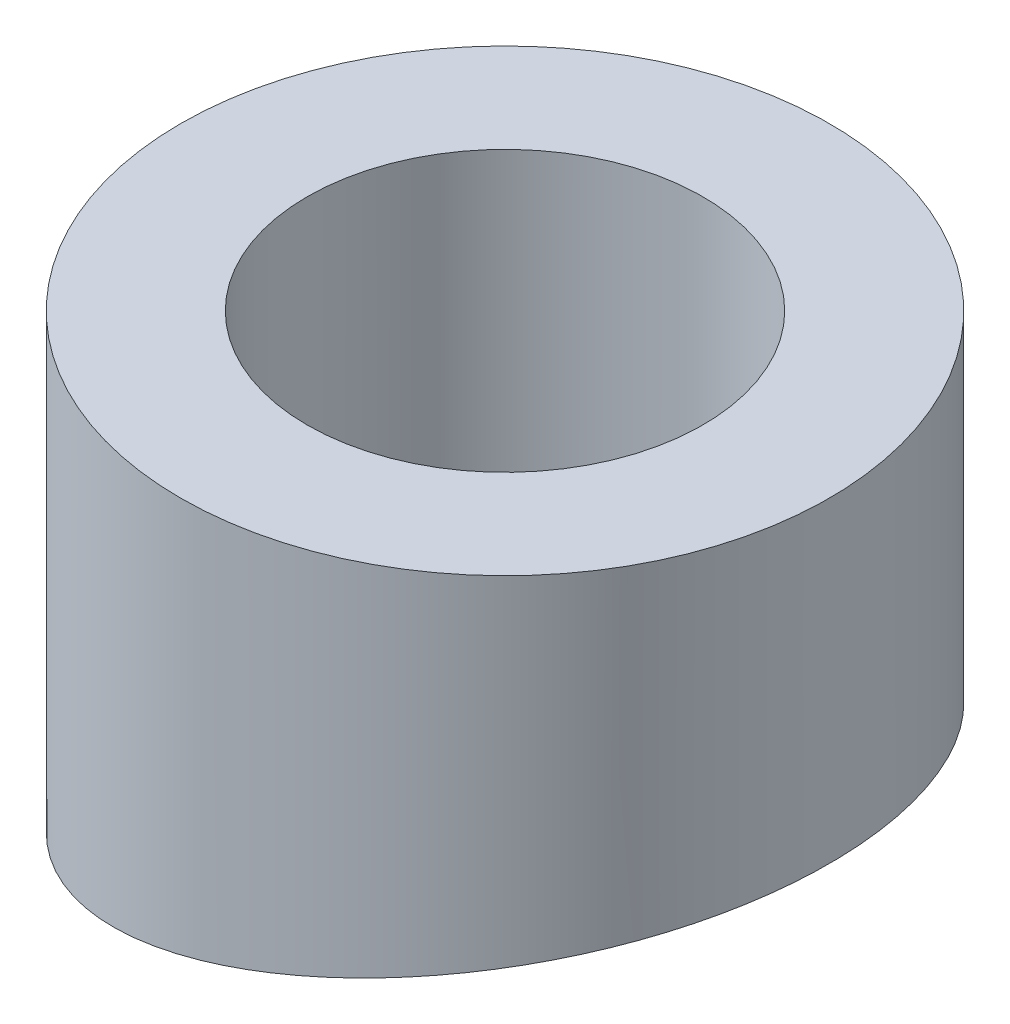
SolidWorks part; units mm, degrees
ref_plane "Front Plane" through (0, 0, 0) normal (0, 0, 1) x (1, 0, 0)
ref_plane "Top Plane" through (0, 0, 0) normal (0, 1, 0) x (1, 0, 0)
ref_plane "Right Plane" through (0, 0, 0) normal (1, 0, 0) x (0, 0, -1)
sketch "Sketch1" plane through (0, 0, 0) normal (0, 1, 0) x (1, 0, 0)
  circle A0 centre (0, 0) radius 6.25
  circle A1 centre (0, 0) radius 10.25
  dimension "D1" = 12.5
  dimension "D2" = 4
extrude "Boss-Extrude1" add sketch "Sketch1" along normal blind 15
sketch "Sketch3" plane through (0, 0, 0) normal (0, 0, 1) x (1, 0, 0)
  line L0 (-10.25, 0) -> (10.25, 5)
  line L1 (10.25, 0) -> (10.25, 15) construction
  line L2 (10.25, 5) -> (10.25, 0)
  line L3 (10.25, 0) -> (-10.25, 0)
  dimension "D1" = 5
extrude "Cut-Extrude1" cut sketch "Sketch3" against normal mid plane 30
